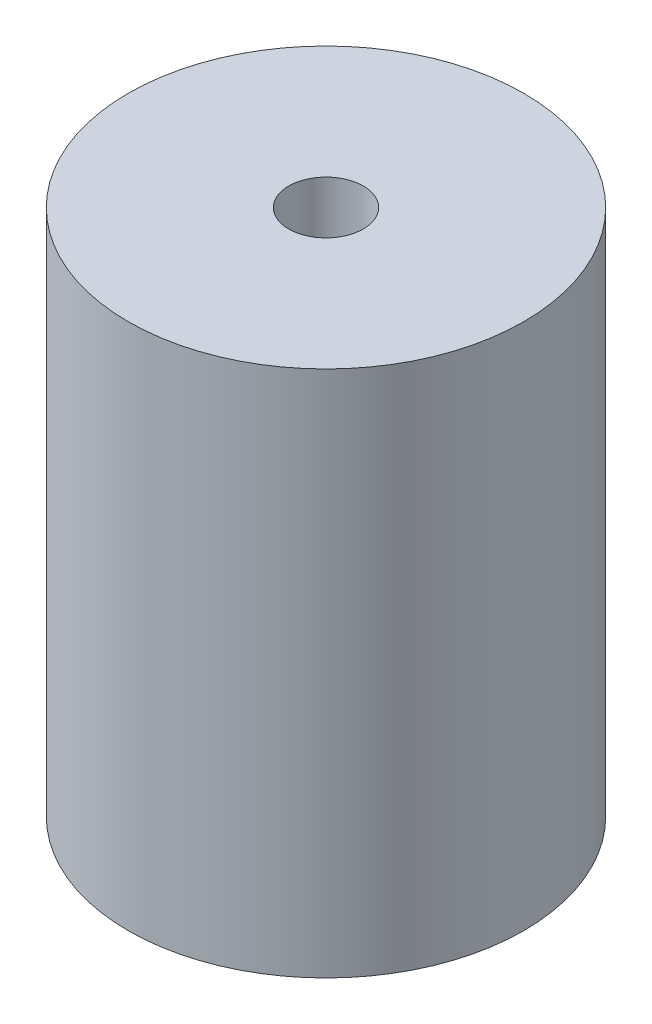
SolidWorks part; units mm, degrees
ref_plane "Front Plane" through (0, 0, 0) normal (0, 0, 1) x (1, 0, 0)
ref_plane "Top Plane" through (0, 0, 0) normal (0, 1, 0) x (1, 0, 0)
ref_plane "Right Plane" through (0, 0, 0) normal (1, 0, 0) x (0, 0, -1)
sketch "Sketch5" plane through (0, 0, 0) normal (0, 1, 0) x (1, 0, 0)
  circle A0 centre (0, 0) radius 38.1
  dimension "D1" = 76.2
extrude "Boss-Extrude1" add sketch "Sketch5" along normal blind 101.6
sketch "Sketch7" plane through (0, 101.6, 0) normal (0, 1, 0) x (1, 0, 0)
  line L1 (5.08, 5.08) -> (-5.08, 5.08)
  line L2 (5.08, 5.08) -> (5.08, -5.08)
  line L3 (5.08, -5.08) -> (-5.08, -5.08)
  line L4 (-5.08, 5.08) -> (-5.08, -5.08)
  line L5 (5.08, 5.08) -> (-5.08, -5.08) construction
  line L6 (5.08, -5.08) -> (-5.08, 5.08) construction
  circle A0 centre (0, 0) radius 7.1842
  point P0 (0, 0)
  point P8 (0, 0)
  dimension "D1" = 10.16
  dimension "D2" = 10.16
extrude "Cut-Extrude1" cut sketch "Sketch7" against normal blind 88.9 contours A0
